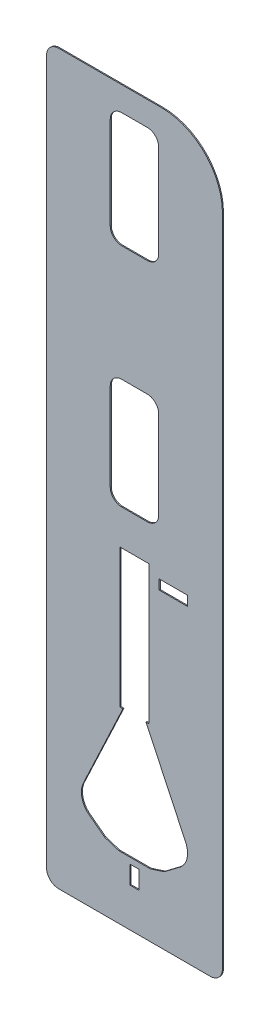
SolidWorks part; units mm, degrees
material "3M 9474LE (300LSE)"
ref_plane "Front Plane" through (0, 0, 0) normal (0, 0, 1) x (1, 0, 0)
ref_plane "Top Plane" through (0, 0, 0) normal (0, 1, 0) x (1, 0, 0)
ref_plane "Right Plane" through (0, 0, 0) normal (1, 0, 0) x (0, 0, -1)
sketch "Sketch13" plane through (0, 0, 0) normal (0, 0, 1) x (1, 0, 0)
  line L0 (0, 60) -> (0, -60) construction
  line L1 (-12.5, 60) -> (4.5, 60)
  line L2 (-14.5, 58) -> (-14.5, -58)
  line L3 (-12.5, -60) -> (12.5, -60)
  line L4 (14.5, 50) -> (14.5, -58)
  line L5 (-14.5, 60) -> (14.5, -60) construction
  line L6 (-14.5, -60) -> (14.5, 60) construction
  line L7 (-14.5, 0) -> (14.5, 0) construction
  line L8 (0, -55) -> (0, 55) construction
  arc A0 (-14.5, -58) -> (-12.5, -60) centre (-12.5, -58) ccw
  arc A1 (12.5, -60) -> (14.5, -58) centre (12.5, -58) ccw
  arc A2 (4.5, 60) -> (14.5, 50) centre (4.5, 50) cw
  arc A3 (-12.5, 60) -> (-14.5, 58) centre (-12.5, 58) ccw
  point P0 (0, 0)
extrude "Boss-Extrude8" add sketch "Sketch13" along normal blind 0.17
sketch "Sketch1" plane through (0, 0, 0.17) normal (0, 0, 1) x (1, 0, 0)
  line L107 (-12.5, -60) -> (12.5, -60) construction
  line L113 (4.5, 60) -> (-12.5, 60) construction
  line L114 (0, 60) -> (0, -60) construction
  line L119 (-4, 46.5) -> (4, 46.5) construction
  line L128 (2.4, -29) -> (1.9, -29) construction
  line L129 (-0.75, -50.6) -> (0.75, -50.6)
  line L130 (-0.75, -50.6) -> (-0.75, -53.6)
  line L132 (4.08, -7.47) -> (8.74, -7.47)
  line L150 (-2.1, 56) -> (2.1, 56)
  line L151 (4, 54.1) -> (4, 38.9)
  line L152 (-2.1, 37) -> (2.1, 37)
  line L153 (-4, 54.1) -> (-4, 38.9)
  line L154 (-2.1, 17.9318) -> (2.1, 17.9318)
  line L155 (4, 16.0318) -> (4, 1.6)
  line L156 (-2.1, -0.3) -> (2.1, -0.3)
  line L157 (-4, 16.0318) -> (-4, 1.6)
  line L158 (2.4, -6.15) -> (-2.4, -6.15)
  line L193 (2.4, -6.15) -> (2.4, -29)
  line L203 (-2.6, -49.6) -> (2.6, -49.6)
  line L204 (4.08, -7.47) -> (4.08, -9.07)
  line L205 (4.08, -9.07) -> (8.74, -9.07)
  line L206 (8.74, -7.47) -> (8.74, -9.07)
  line L207 (4.08, -7.47) -> (8.74, -9.07) construction
  line L208 (4.08, -9.07) -> (8.74, -7.47) construction
  line L209 (-0.75, -53.6) -> (0.75, -53.6)
  line L210 (0.75, -50.6) -> (0.75, -53.6)
  line L211 (-0.75, -50.6) -> (0.75, -53.6) construction
  line L212 (-0.75, -53.6) -> (0.75, -50.6) construction
  line L213 (8.375, -42.75) -> (1.9, -29) construction
  line L214 (4.925, -48.85) -> (7.4, -46.9731) construction
  line L215 (2.6, -49.6) -> (4.925, -48.85) construction
  line L216 (-4.925, -48.85) -> (-2.6, -49.6) construction
  line L217 (-7.4, -46.9731) -> (-4.925, -48.85) construction
  line L218 (-1.9, -29) -> (-8.375, -42.75) construction
  line L219 (-2.4, -29) -> (-1.9, -29) construction
  line L220 (2.4, -29) -> (1.9, -29)
  line L221 (8.375, -42.75) -> (1.9, -29)
  line L222 (4.925, -48.85) -> (7.4, -46.9731)
  line L223 (2.6, -49.6) -> (4.925, -48.85)
  line L224 (-4.925, -48.85) -> (-2.6, -49.6)
  line L225 (-7.4, -46.9731) -> (-4.925, -48.85)
  line L226 (-1.9, -29) -> (-8.375, -42.75)
  line L227 (-2.4, -29) -> (-1.9, -29)
  line L228 (-2.4, -4.42) -> (-2.4, -29) construction
  line L229 (-2.4, -6.15) -> (-2.4, -29)
  line L230 (2.5, 55) -> (-2.5, 55) construction
  line L231 (2.5, 38) -> (-2.5, 38) construction
  line L232 (4, 51) -> (4, 2.5) construction
  line L233 (-2.5, 16.9318) -> (2.5, 16.9318) construction
  arc A38 (4, 54.1) -> (2.1, 56) centre (2.1, 54.1) ccw
  arc A39 (-4, 54.1) -> (-2.1, 56) centre (-2.1, 54.1) cw
  arc A40 (-4, 38.9) -> (-2.1, 37) centre (-2.1, 38.9) ccw
  arc A41 (4, 38.9) -> (2.1, 37) centre (2.1, 38.9) cw
  arc A42 (4, 16.0318) -> (2.1, 17.9318) centre (2.1, 16.0318) ccw
  arc A43 (-4, 16.0318) -> (-2.1, 17.9318) centre (-2.1, 16.0318) cw
  arc A44 (-4, 1.6) -> (-2.1, -0.3) centre (-2.1, 1.6) ccw
  arc A45 (4, 1.6) -> (2.1, -0.3) centre (2.1, 1.6) cw
  spline S4 degree 3 poles (-2211.0014, 1964.9254) (1967.9153, -2344.8373) (-1653.2812, 2485.386) (1333.8003, -2728.018) knots -35.229961 -35.229961 -35.229961 -35.229961 41.331958 41.331958 41.331958 41.331958 only from (8.75, -44.3) to (8.375, -42.75) construction
  spline S5 degree 3 poles (1576.4055, 2503.5485) (-1886.2128, -2403.2166) (2181.5396, 2053.8609) (-2397.4558, -1825.6873) knots -16.257706 -16.257706 -16.257706 -16.257706 22.929369 22.929369 22.929369 22.929369 only from (7.4, -46.9731) to (8.75, -44.3) construction
  spline S6 degree 3 poles (2397.5108, -1825.734) (-2181.5509, 2053.8785) (1886.1887, -2403.1947) (-1576.357, 2503.4798) knots -15.931221 -15.931221 -15.931221 -15.931221 23.255828 23.255828 23.255828 23.255828 only from (-8.75, -44.3) to (-7.4, -46.9731) construction
  spline S7 degree 3 poles (-1333.8598, -2728.1219) (1653.3192, 2485.4325) (-1967.9185, -2344.8332) (2210.959, 1964.8816) knots -36.332467 -36.332467 -36.332467 -36.332467 40.229701 40.229701 40.229701 40.229701 only from (-8.375, -42.75) to (-8.75, -44.3) construction
  spline S8 degree 3 poles (8.75, -44.3) (8.7497, -43.7369) (8.614, -43.206) (8.375, -42.75) knots 2 2 2 2 3 3 3 3
  spline S9 degree 3 poles (7.4, -46.9731) (8.2114, -46.4163) (8.7506, -45.4277) (8.75, -44.3) knots 3 3 3 3 3.998305 3.998305 3.998305 3.998305
  spline S10 degree 3 poles (-8.75, -44.3) (-8.7506, -45.4277) (-8.2114, -46.4163) (-7.4, -46.9731) knots 3 3 3 3 3.998305 3.998305 3.998305 3.998305
  spline S11 degree 3 poles (-8.375, -42.75) (-8.614, -43.206) (-8.7497, -43.7369) (-8.75, -44.3) knots 2 2 2 2 3 3 3 3
  point P9 (0, -52.1)
  point P38 (6.41, -8.27)
  point P43 (0, 0)
  dimension "D10" = 1
  dimension "D2" = 5.85
  dimension "D1" = 1.9
  dimension "D3" = 1
  dimension "D5" = 53.85
  dimension "D4" = 1
  dimension "D6" = 4.66
  dimension "D7" = 1.6
  dimension "D8" = 1.68
  dimension "D9" = 1.32
  dimension "D11" = 3
  dimension "D12" = 1.5
  dimension "D13" = 19
  dimension "D14" = 18.2318
extrude "Cut-Extrude1" cut sketch "Sketch1" against normal through all
